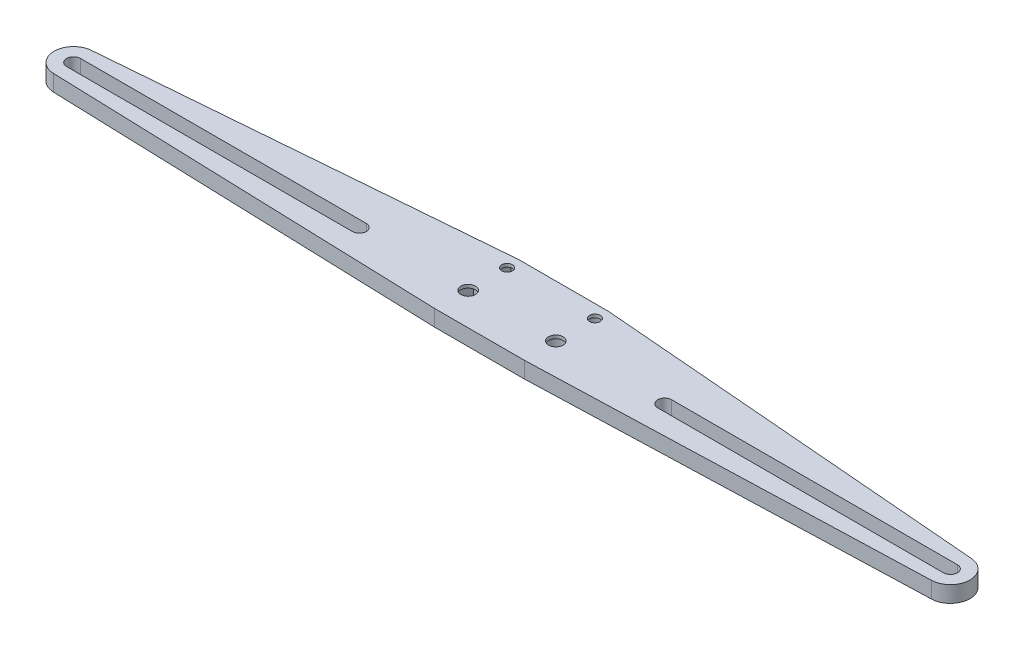
SolidWorks part; units mm, degrees
ref_plane "Front Plane" through (0, 0, 0) normal (0, 0, 1) x (1, 0, 0)
ref_plane "Top Plane" through (0, 0, 0) normal (0, 1, 0) x (1, 0, 0)
ref_plane "Right Plane" through (0, 0, 0) normal (1, 0, 0) x (0, 0, -1)
sketch "Sketch1" plane through (0, 0, 0) normal (0, 1, 0) x (1, 0, 0)
  line L0 (0, 6) -> (0, -6)
  line L1 (0, -6) -> (135, -6)
  line L2 (0, 6) -> (135, 6)
  line L3 (47, 2.15) -> (135, 2.15)
  line L4 (135, -2.15) -> (47, -2.15)
  line L5 (9.5, 6) -> (9.5, 12)
  line L6 (17.5, 6) -> (17.5, 12)
  line L7 (13.8279, 15.9865) -> (135.4918, 5.9798)
  line L8 (0, -6) -> (0, -10)
  line L9 (0, -10) -> (13.8279, -10)
  line L10 (13.8279, -10) -> (135.1978, -5.9967)
  line L11 (13.5, 0) -> (7, 0) construction
  line L12 (13.8279, 15.9865) -> (0, 15.9865)
  line L13 (0, 15.9865) -> (0, 6)
  arc A0 (135, 6) -> (135, -6) centre (135, 0) cw
  circle A1 centre (135, 0) radius 2.15
  circle A2 centre (47, 0) radius 2.15
  arc A3 (9.5, 12) -> (17.5, 12) centre (13.5, 12) cw
  circle A4 centre (13.5, 12) radius 1.65
  circle A5 centre (13.5, 0) radius 2.25
  circle A6 centre (13.5, 0) radius 6.5 construction
  point P6 (0, 0)
  dimension "D1" = 12
  dimension "D2" = 47
  dimension "D5" = 8
  dimension "D7" = 3.3
  dimension "D10" = 7
  dimension "D11" = 13
  dimension "D12" = 4.5
  dimension "D3" = 135
  dimension "D4" = 4.3
  dimension "D6" = 13.5
  dimension "D8" = 6
  dimension "D9" = 4
extrude "Boss-Extrude1" add sketch "Sketch1" along normal blind 5 contours A0 L2 L0 L1 A2 L3 A1 L4 | A3 L5 L2 L6 A4 | L7 A3 L6 L2 A0 | L10 A0 L1 L8 L9 | L5 A3 L12 L13 L2
mirror "Mirror1" about plane through (0, 0, 0) normal (1, 0, 0) of bodies 101
sketch "Sketch3" plane through (0, 0, 0) normal (0, 1, 0) x (1, 0, 0)
  line L1 (-9.1699, 0) -> (-11.3349, 3.75)
  line L2 (-11.3349, 3.75) -> (-15.6651, 3.75)
  line L3 (-15.6651, 3.75) -> (-17.8301, 0)
  line L4 (-17.8301, 0) -> (-15.6651, -3.75)
  line L5 (-15.6651, -3.75) -> (-11.3349, -3.75)
  line L6 (-11.3349, -3.75) -> (-9.1699, 0)
  line L7 (-10.0359, 12) -> (-11.7679, 15)
  line L8 (-11.7679, 15) -> (-15.2321, 15)
  line L9 (-15.2321, 15) -> (-16.9641, 12)
  line L10 (-16.9641, 12) -> (-15.2321, 9)
  line L11 (-15.2321, 9) -> (-11.7679, 9)
  line L12 (-11.7679, 9) -> (-10.0359, 12)
  circle A0 centre (13.5, 0) radius 3.75
  circle A1 centre (-13.5, 0) radius 3.75 construction
  circle A2 centre (13.5, 12) radius 3
  circle A3 centre (-13.5, 12) radius 3 construction
  dimension "D1" = 7.5
  dimension "D3" = 6
  dimension "D2" = 7.5
  dimension "D4" = 6
extrude "Cut-Extrude1" cut sketch "Sketch3" along normal blind 4
